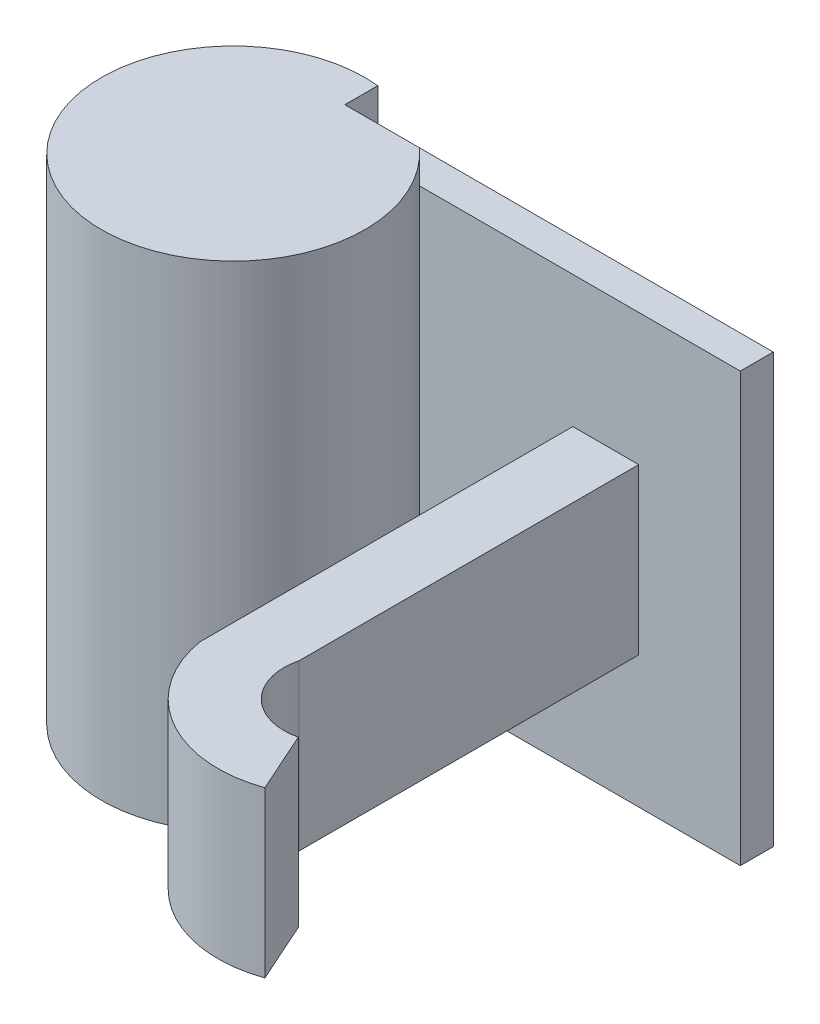
SolidWorks part; units mm, degrees
ref_plane "Front Plane" through (0, 0, 0) normal (0, 0, 1) x (1, 0, 0)
ref_plane "Top Plane" through (0, 0, 0) normal (0, 1, 0) x (1, 0, 0)
ref_plane "Right Plane" through (0, 0, 0) normal (1, 0, 0) x (0, 0, -1)
sketch "Sketch1" plane through (0, 0, 0) normal (0, 1, 0) x (1, 0, 0)
  line L0 (-19.1833, 35.8619) -> (-18.3601, 34.0242)
  line L1 (-30.0975, 49.1886) -> (-18.0975, 49.1886)
  line L2 (-30.0975, 49.1886) -> (-30.0975, 48.1886)
  line L3 (-30.0975, 48.1886) -> (-18.0975, 48.1886)
  line L4 (-18.0975, 49.1886) -> (-18.0975, 48.1886)
  line L5 (-23.1795, 48.1886) -> (-21.1795, 48.1886)
  line L6 (-23.1795, 48.1886) -> (-23.1795, 36.87)
  line L7 (-23.1795, 36.87) -> (-21.1795, 36.87)
  line L8 (-21.1795, 48.1886) -> (-21.1795, 36.87)
  circle A0 centre (-30.5088, 45.2098) radius 4
  circle A1 centre (-19.5743, 37.4718) radius 3.6551
  circle A2 centre (-19.5743, 37.4718) radius 1.6567
  dimension "D1" = 8
  dimension "D2" = 1
  dimension "D3" = 12
  dimension "D4" = 2
extrude "Boss-Extrude1" add sketch "Sketch1" along normal blind 15 contours L2 A0 L3 | A0 L3 L4 L1 | L3 A0 L2 | A1 L8 L3 L6 | A2 L8 A1 L6 L7 | A2 L8 L7 A1 L0
sketch "Sketch2" plane through (0, 0, -49.1886) normal (0, 0, -1) x (-1, 0, 0)
  line L1 (18.0975, 15) -> (30.0975, 15)
  line L2 (18.0975, 15) -> (18.0975, 14)
  line L3 (18.0975, 14) -> (30.0975, 14)
  line L4 (30.0975, 15) -> (30.0975, 14)
  line L5 (18.0975, 1) -> (30.0975, 1)
  line L6 (18.0975, 1) -> (18.0975, 0)
  line L7 (18.0975, 0) -> (30.0975, 0)
  line L8 (30.0975, 1) -> (30.0975, 0)
  dimension "D1" = 1
  dimension "D2" = 1
extrude "Cut-Extrude1" cut sketch "Sketch2" against normal blind 1
sketch "Sketch5" plane through (0, 0, -48.1886) normal (0, 0, -1) x (-1, 0, 0)
  line L1 (23.8145, 16.3513) -> (17.7857, 16.3513)
  line L2 (23.8145, 16.3513) -> (23.8145, 10)
  line L3 (23.8145, 10) -> (17.7857, 10)
  line L4 (17.7857, 16.3513) -> (17.7857, 10)
  line L5 (23.7626, -1.2191) -> (17.7857, -1.2191)
  line L6 (23.7626, -1.2191) -> (23.7626, 5)
  line L7 (23.7626, 5) -> (17.7857, 5)
  line L8 (17.7857, -1.2191) -> (17.7857, 5)
  line L10 (18.0975, 14) -> (30.0975, 14) construction
  line L11 (30.0975, 1) -> (18.0975, 1) construction
  dimension "D1" = 4
  dimension "D2" = 4
extrude "Cut-Extrude2" cut sketch "Sketch5" against normal blind 21
